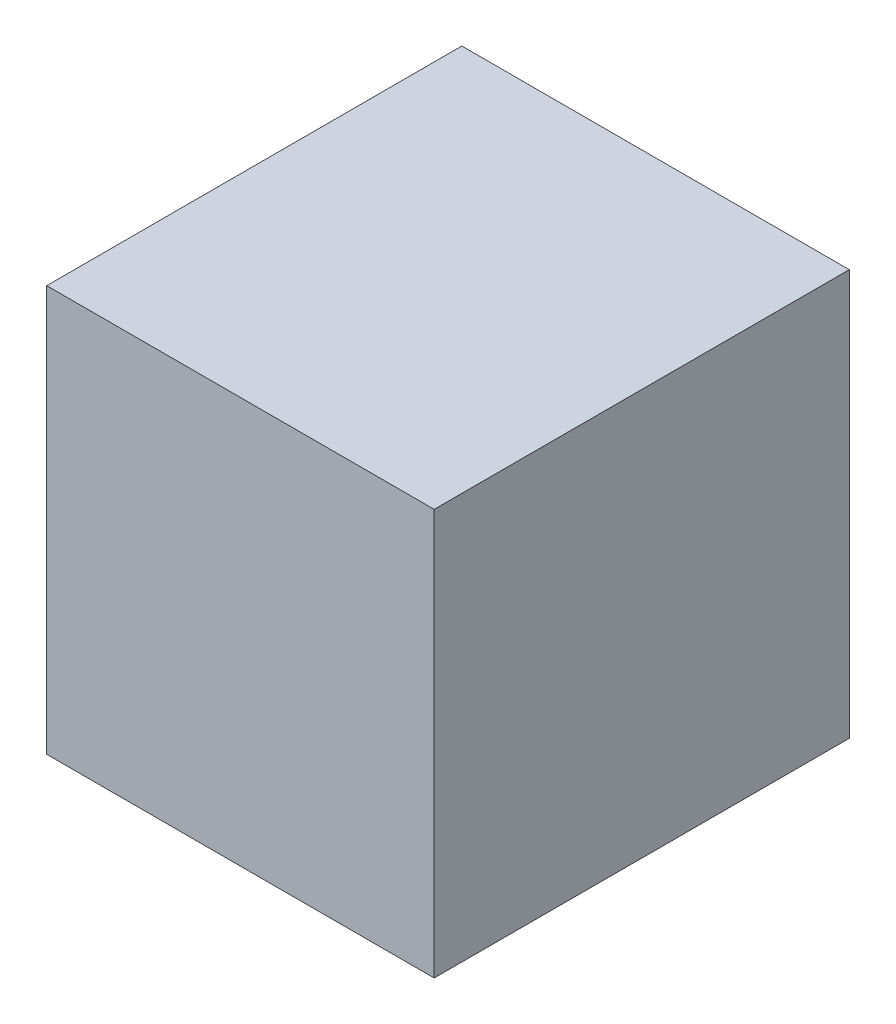
SolidWorks part; units mm, degrees
ref_plane "Front Plane" through (0, 0, 0) normal (0, 0, 1) x (1, 0, 0)
ref_plane "Top Plane" through (0, 0, 0) normal (0, 1, 0) x (1, 0, 0)
ref_plane "Right Plane" through (0, 0, 0) normal (1, 0, 0) x (0, 0, -1)
sketch "Sketch1" plane through (0, 0, 0) normal (0, 1, 0) x (1, 0, 0)
  line L1 (42, -45) -> (-42, -45)
  line L2 (42, -45) -> (42, 45)
  line L3 (42, 45) -> (-42, 45)
  line L4 (-42, -45) -> (-42, 45)
  line L5 (42, -45) -> (-42, 45) construction
  line L6 (42, 45) -> (-42, -45) construction
  point P0 (0, 0)
  dimension "D1" = 90
  dimension "D2" = 84
extrude "Boss-Extrude1" add sketch "Sketch1" along normal blind 88
